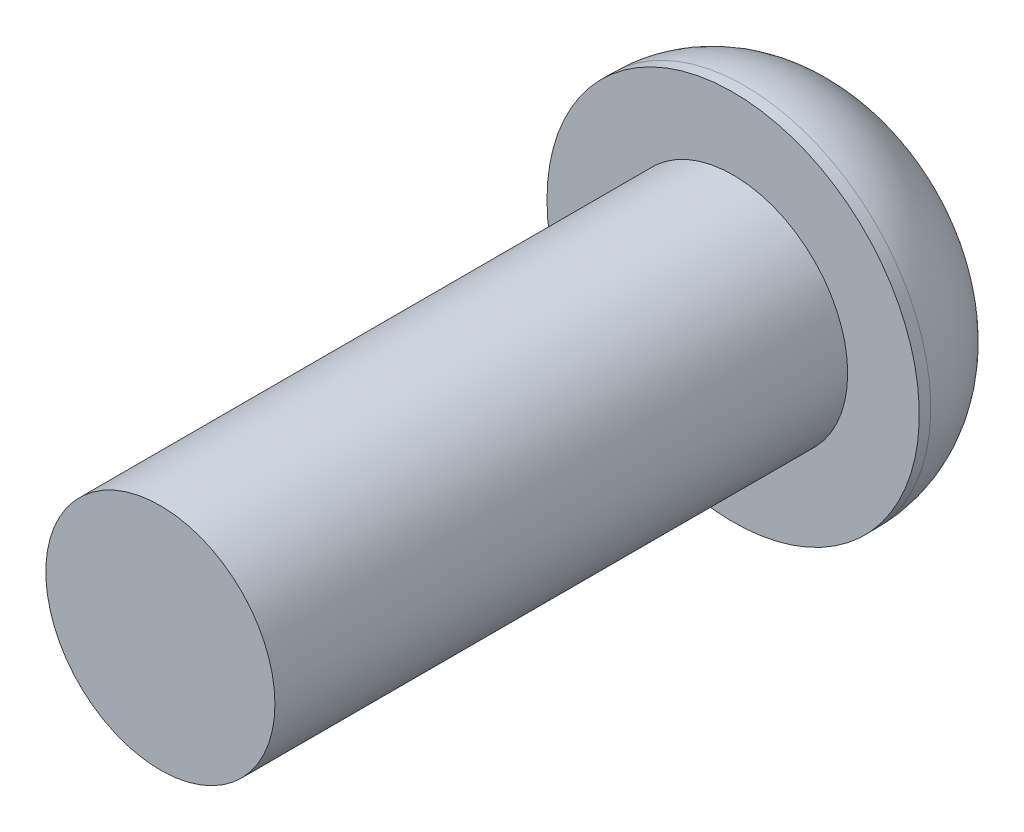
SolidWorks part; units mm, degrees
ref_plane "前视基准面" through (0, 0, 0) normal (0, 0, 1) x (1, 0, 0)
ref_plane "上视基准面" through (0, 0, 0) normal (0, 1, 0) x (1, 0, 0)
ref_plane "右视基准面" through (0, 0, 0) normal (1, 0, 0) x (0, 0, -1)
sketch "草图1" plane through (0, 0, 0) normal (0, 0, 1) x (1, 0, 0)
  circle A0 centre (0, 0) radius 2
  dimension "D1" = 4
extrude "凸台-拉伸1" add sketch "草图1" along normal blind 10
sketch "草图2" plane through (0, 0, 0) normal (0, 0, -1) x (-1, 0, 0)
  circle A0 centre (0, 0) radius 3.25
  dimension "D1" = 6.5
extrude "凸台-拉伸2" add sketch "草图2" along normal blind 2.2
fillet "圆角1" radius 2 1 edges at (-3.25, 0, -2.2)
sketch "草图3" plane through (0, 0, -2.2) normal (0, 0, -1) x (-1, 0, 0)
  line L0 (0, 3.24) -> (0, -3.24) construction
  line L1 (-3.24, 0) -> (3.24, 0) construction
  line L2 (-3.24, 0.25) -> (3.24, 0.25) construction
  line L3 (0.25, 3.24) -> (0.25, -3.24) construction
  line L4 (-3.24, -0.25) -> (3.24, -0.25) construction
  line L5 (-0.25, 3.24) -> (-0.25, -3.24) construction
  line L7 (3.24, 0.25) -> (3.24, -0.25)
  line L8 (-0.25, 3.24) -> (0.25, 3.24)
  line L10 (-0.25, 3.24) -> (-0.25, 0.25)
  line L11 (0.25, 3.24) -> (0.25, 0.25)
  line L12 (3.24, 0.25) -> (0.25, 0.25)
  line L13 (3.24, -0.25) -> (0.25, -0.25)
  line L15 (0.25, -3.24) -> (0.25, -0.25)
  line L16 (-0.25, -3.24) -> (-0.25, -0.25)
  line L17 (0.25, -3.24) -> (-0.25, -3.24)
  line L18 (-3.24, -0.25) -> (-0.25, -0.25)
  line L19 (-3.24, 0.25) -> (-0.25, 0.25)
  line L20 (-3.24, -0.25) -> (-3.24, 0.25)
  line L21 (3.24, 0.25) -> (3.24, -0.25) [skipped]
  circle A1 centre (0, 0) radius 3.24 construction
  dimension "D1" = 0.25
  dimension "D2" = 0.25
  dimension "D3" = 4
extrude "切除-拉伸1" cut sketch "草图3" against normal blind 0.5
